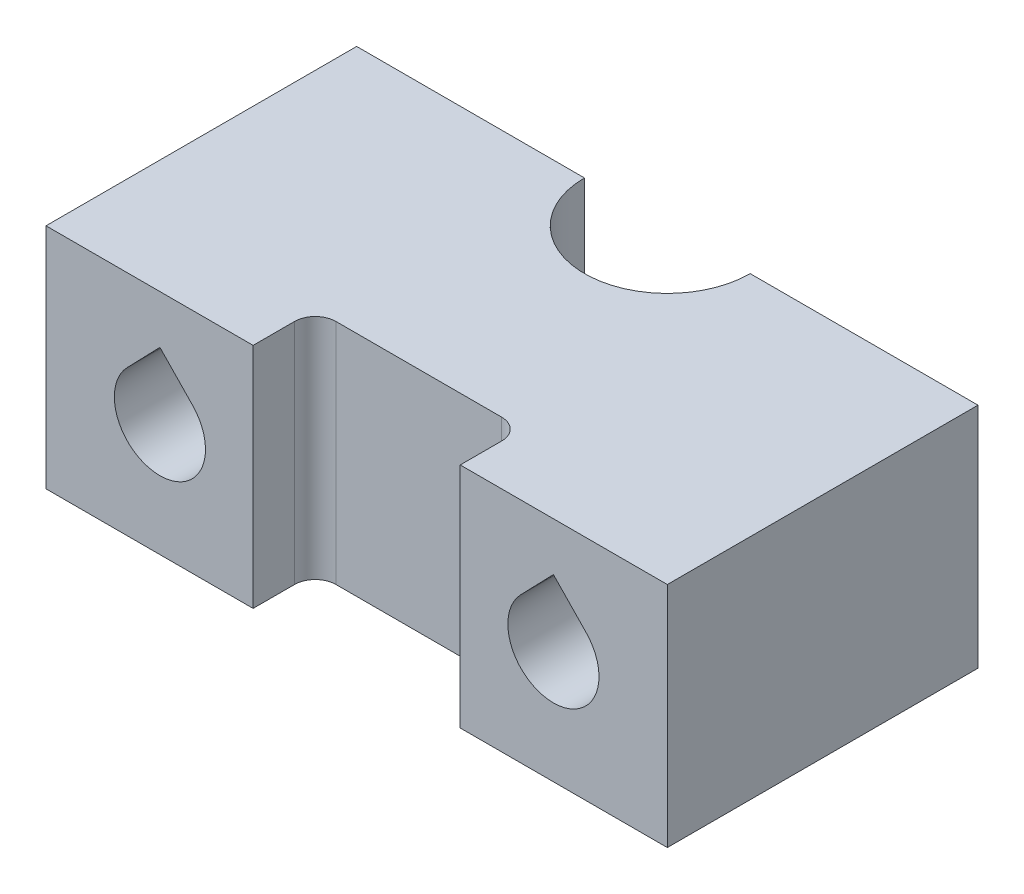
SolidWorks part; units mm, degrees
ref_plane "Front Plane" through (0, 0, 0) normal (0, 0, 1) x (1, 0, 0)
ref_plane "Top Plane" through (0, 0, 0) normal (0, 1, 0) x (1, 0, 0)
ref_plane "Right Plane" through (0, 0, 0) normal (1, 0, 0) x (0, 0, -1)
ref_plane "Plane1" through (0, -36.5, 0) normal (0, -1, 0) x (1, 0, 0)
sketch "Sketch1" plane through (0, -36.5, 0) normal (0, -1, 0) x (1, 0, 0)
  line L0 (-19.5, 25) -> (-19.5, 40)
  line L1 (-19.5, 40) -> (-49.5, 40)
  line L2 (-49.5, 40) -> (-49.5, 25)
  line L3 (-49.5, 25) -> (-19.5, 25)
extrude "Boss-Extrude1" add sketch "Sketch1" against normal blind 11
sketch "Sketch2" plane through (0, -25.5, 0) normal (0, 1, 0) x (-1, 0, 0)
  line L0 (29.5, 40) -> (29.5, 37)
  line L1 (29.5, 37) -> (39.5, 37)
  line L2 (39.5, 37) -> (39.5, 40)
  line L3 (39.5, 40) -> (29.5, 40)
extrude "Cut-Extrude1" cut sketch "Sketch2" against normal through all
sketch "Sketch3" plane through (0, 0, 25) normal (0, 0, -1) x (-1, 0, 0)
  line L0 (45.5825, -29.4718) -> (44, -27.833)
  line L1 (44, -27.833) -> (42.4175, -29.4718)
  arc A0 (42.4175, -29.4718) -> (45.5825, -29.4718) centre (44, -31) ccw
extrude "Cut-Extrude2" cut sketch "Sketch3" against normal through all
sketch "Sketch4" plane through (0, 0, 40) normal (0, 0, 1) x (1, 0, 0)
  line L0 (-25, -27.833) -> (-26.5825, -29.4718)
  line L1 (-23.4175, -29.4718) -> (-25, -27.833)
  arc A0 (-26.5825, -29.4718) -> (-23.4175, -29.4718) centre (-25, -31) ccw
extrude "Cut-Extrude3" cut sketch "Sketch4" against normal through all
hole_wizard "Hole1" positions "Sketch6" profile "Sketch5" legacy
sketch "Sketch6" plane through (0, -36.5, 0) normal (0, -1, 0) x (1, 0, 0)
  point P0 (-34.5, 25)
sketch "Sketch5" plane through (-34.5, -36.5, 25) normal (1, 0, 0) x (0, 0, -1)
  line L0 (0, 0) -> (0, 11)
  line L1 (0, 11) -> (4, 11)
  line L2 (4, 11) -> (4, 0)
  line L3 (4, 0) -> (0, 0)
  line L4 (0, 110) -> (0, -10) construction
  dimension "Diameter" = 8
  dimension "Depth" = 11
fillet "Fillet1" radius 1 1 edges at (-39.5, -31, 37)
fillet "Fillet2" radius 1 1 edges at (-29.5, -31, 37)
